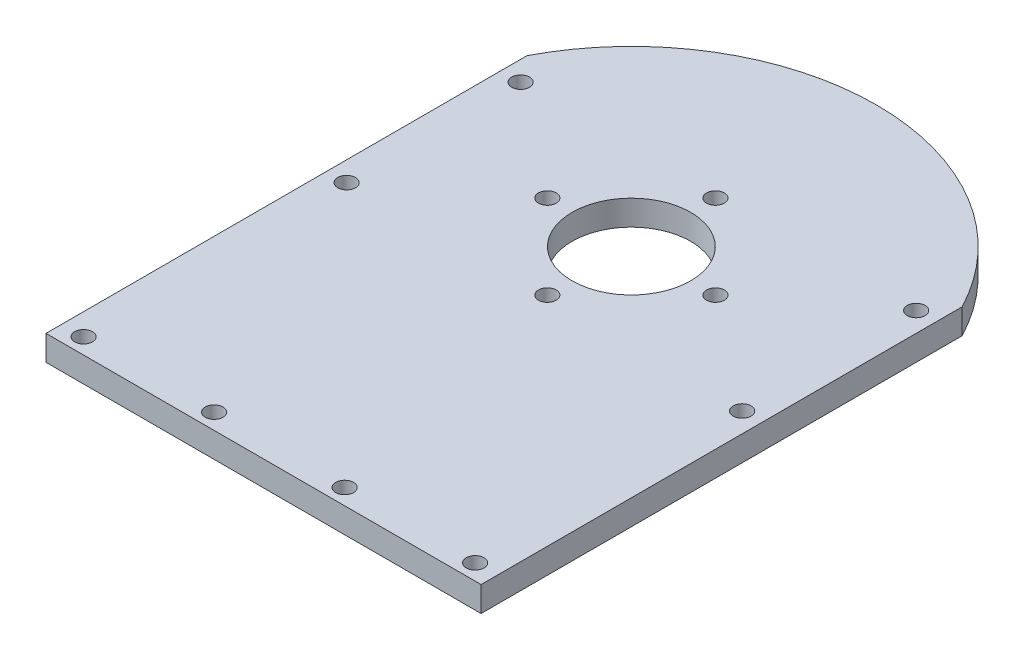
SolidWorks part; units mm, degrees
material "6061 Alloy"
ref_plane "Front Plane" through (0, 0, 0) normal (0, 0, 1) x (1, 0, 0)
ref_plane "Top Plane" through (0, 0, 0) normal (0, 1, 0) x (1, 0, 0)
ref_plane "Right Plane" through (0, 0, 0) normal (1, 0, 0) x (0, 0, -1)
sketch "Sketch1" plane through (0, 0, 0) normal (0, 1, 0) x (1, 0, 0)
  line L0 (-5, 34) -> (105, 34) construction
  line L1 (50, 84) -> (50, -5) construction
  line L2 (-5, -16) -> (-5, 84)
  line L3 (-5, 84) -> (105, 84)
  line L4 (105, -16) -> (105, 84)
  line L6 (-5, -16) -> (-5, -71)
  line L7 (-5, -71) -> (105, -71)
  line L8 (105, -16) -> (105, -71)
  circle A0 centre (0, 0) radius 2.25
  circle A1 centre (0, 44) radius 2.25
  circle A2 centre (100, 44) radius 2.25
  circle A3 centre (100, 0) radius 2.25
  circle A4 centre (50, 43.25) radius 2.25
  circle A5 centre (71.25, 22) radius 2.25
  circle A6 centre (50, 0.75) radius 2.25
  circle A7 centre (28.75, 22) radius 2.25
  point P21 (50, 34)
  point P31 (50, 22)
  dimension "D7" = 155
  dimension "D8" = 4
  dimension "D5" = 4.5
  dimension "D2" = 100
  dimension "D3" = 5
  dimension "D4" = 40
  dimension "D6" = 50
extrude "Boss-Extrude1" add sketch "Sketch1" along normal blind 6.35
sketch "Sketch2" plane through (0, 6.35, 0) normal (0, 1, 0) x (1, 0, 0)
  circle A0 centre (50, 22) radius 15
extrude "Cut-Extrude1" cut sketch "Sketch2" against normal blind 10
sketch "Sketch3" plane through (0, 6.35, 0) normal (0, 1, 0) x (1, 0, 0)
  line L0 (-11.8793, 18.133) -> (-19.1225, 134.0372)
  line L1 (-19.1225, 134.0372) -> (176.3644, 135.7142)
  line L2 (176.3644, 135.7142) -> (111.2275, 31.7565)
  arc A0 (111.2275, 31.7565) -> (-11.8793, 18.133) centre (50, 22) ccw
extrude "Cut-Extrude2" cut sketch "Sketch3" against normal blind 60
sketch "Sketch4" plane through (0, 0, 0) normal (0, -1, 0) x (1, 0, 0)
  line L0 (-5, -50.6182) -> (-5, 71) construction
  line L1 (-5, 71) -> (105, 71) construction
  circle A0 centre (99.5, 67) radius 2.25
  circle A1 centre (0.5, 67) radius 2.25
  circle A2 centre (33.5, 67) radius 2.25
  circle A3 centre (66.5, 67) radius 2.25
  point P0 (0.5, 67)
  point P1 (66.5, 67)
  point P2 (99.5, 67)
  point P3 (33.5, 67)
  dimension "D1" = 5.5
  dimension "D2" = 33
  dimension "D3" = 33
  dimension "D4" = 33
  dimension "D5" = 4
extrude "Cut-Extrude3" cut sketch "Sketch4" against normal blind 10
